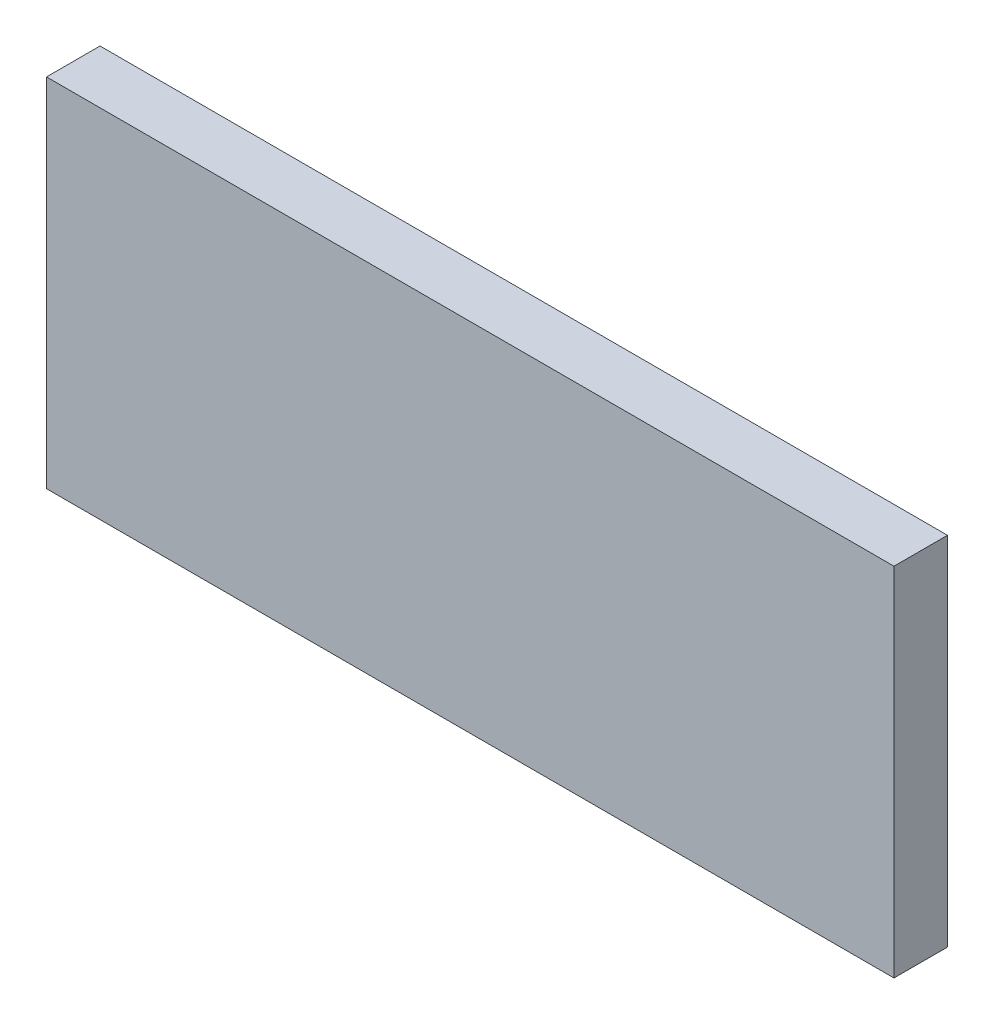
SolidWorks part; units mm, degrees
ref_plane "Front Plane" through (0, 0, 0) normal (0, 0, 1) x (1, 0, 0)
ref_plane "Top Plane" through (0, 0, 0) normal (0, 1, 0) x (1, 0, 0)
ref_plane "Right Plane" through (0, 0, 0) normal (1, 0, 0) x (0, 0, -1)
sketch "Sketch1" plane through (0, 0, 0) normal (0, 0, 1) x (1, 0, 0)
  line L1 (71.7706, 33.4815) -> (-86.5369, 33.4815)
  line L2 (71.7706, 33.4815) -> (71.7706, -33.1381)
  line L3 (71.7706, -33.1381) -> (-86.5369, -33.1381)
  line L4 (-86.5369, 33.4815) -> (-86.5369, -33.1381)
extrude "Boss-Extrude1" add sketch "Sketch1" along normal blind 10
